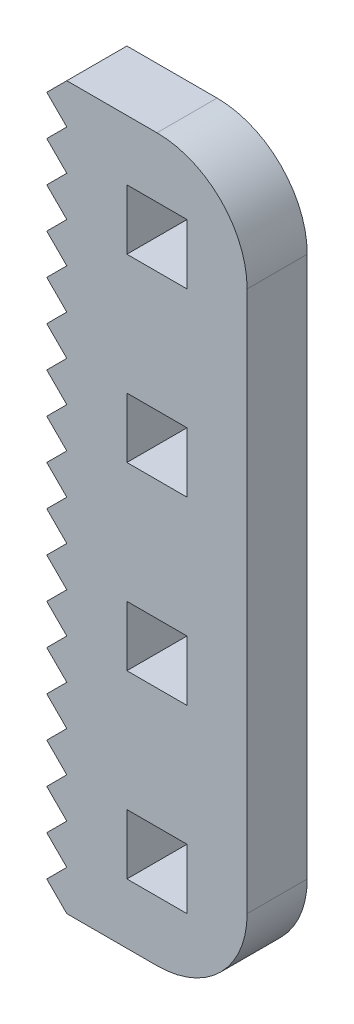
SolidWorks part; units mm, degrees
ref_plane "Alzado" through (0, 0, 0) normal (0, 0, 1) x (1, 0, 0)
ref_plane "Planta" through (0, 0, 0) normal (0, 1, 0) x (1, 0, 0)
ref_plane "Vista lateral" through (0, 0, 0) normal (1, 0, 0) x (0, 0, -1)
sketch "Model" plane through (0, 0, 0) normal (0, 0, 1) x (1, 0, 0)
  line L0 (9.9257, 288.1644) -> (8.9257, 289.1644)
  line L1 (8.9257, 289.1644) -> (9.9257, 290.1644)
  line L2 (9.9257, 286.1644) -> (8.9257, 287.1644)
  line L3 (8.9257, 287.1644) -> (9.9257, 288.1644)
  line L4 (9.9257, 284.1644) -> (8.9257, 285.1644)
  line L5 (8.9257, 285.1644) -> (9.9257, 286.1644)
  line L6 (9.9257, 282.1644) -> (8.9257, 283.1644)
  line L7 (8.9257, 283.1644) -> (9.9257, 284.1644)
  line L8 (9.9257, 280.1644) -> (8.9257, 281.1644)
  line L9 (8.9257, 281.1644) -> (9.9257, 282.1644)
  line L10 (9.9257, 278.1644) -> (8.9257, 279.1644)
  line L11 (8.9257, 279.1644) -> (9.9257, 280.1644)
  line L12 (9.9257, 276.1644) -> (8.9257, 277.1644)
  line L13 (8.9257, 277.1644) -> (9.9257, 278.1644)
  line L14 (9.9257, 274.1644) -> (8.9257, 275.1644)
  line L15 (8.9257, 275.1644) -> (9.9257, 276.1644)
  line L16 (9.9257, 272.1644) -> (8.9257, 273.1644)
  line L17 (8.9257, 273.1644) -> (9.9257, 274.1644)
  line L18 (9.9257, 270.1644) -> (8.9257, 271.1644)
  line L19 (8.9257, 271.1644) -> (9.9257, 272.1644)
  line L20 (9.9257, 268.1644) -> (8.9257, 269.1644)
  line L21 (8.9257, 269.1644) -> (9.9257, 270.1644)
  line L22 (9.9257, 266.1644) -> (8.9257, 267.1644)
  line L23 (8.9257, 267.1644) -> (9.9257, 268.1644)
  line L24 (9.9257, 264.1644) -> (8.9257, 265.1644)
  line L25 (8.9257, 265.1644) -> (9.9257, 266.1644)
  line L26 (9.9257, 262.1644) -> (8.9257, 263.1644)
  line L27 (8.9257, 263.1644) -> (9.9257, 264.1644)
  line L28 (9.9257, 260.1644) -> (8.9257, 261.1644)
  line L29 (8.9257, 261.1644) -> (9.9257, 262.1644)
  line L30 (9.9257, 258.1644) -> (8.9257, 259.1644)
  line L31 (8.9257, 259.1644) -> (9.9257, 260.1644)
  line L32 (9.9257, 256.1644) -> (8.9257, 257.1644)
  line L33 (8.9257, 257.1644) -> (9.9257, 258.1644)
  line L34 (9.9257, 254.1644) -> (8.9257, 255.1644)
  line L35 (8.9257, 255.1644) -> (9.9257, 256.1644)
  line L36 (12.9257, 287.1644) -> (12.9257, 284.1644)
  line L37 (15.9257, 287.1644) -> (12.9257, 287.1644)
  line L38 (15.9257, 284.1644) -> (15.9257, 287.1644)
  line L39 (12.9257, 284.1644) -> (15.9257, 284.1644)
  line L40 (12.9257, 278.1644) -> (12.9257, 275.1644)
  line L41 (15.9257, 278.1644) -> (12.9257, 278.1644)
  line L42 (15.9257, 275.1644) -> (15.9257, 278.1644)
  line L43 (12.9257, 275.1644) -> (15.9257, 275.1644)
  line L44 (12.9257, 260.1644) -> (12.9257, 257.1644)
  line L45 (15.9257, 260.1644) -> (12.9257, 260.1644)
  line L46 (15.9257, 257.1644) -> (15.9257, 260.1644)
  line L47 (12.9257, 257.1644) -> (15.9257, 257.1644)
  line L48 (12.9257, 269.1644) -> (12.9257, 266.1644)
  line L49 (15.9257, 269.1644) -> (12.9257, 269.1644)
  line L50 (15.9257, 266.1644) -> (15.9257, 269.1644)
  line L51 (12.9257, 266.1644) -> (15.9257, 266.1644)
  line L52 (18.9257, 258.6644) -> (18.9257, 285.6644)
  line L53 (14.4257, 290.1644) -> (9.9257, 290.1644)
  line L54 (14.4257, 254.1644) -> (9.9257, 254.1644)
  arc A0 (18.9257, 285.6644) -> (14.4257, 290.1644) centre (14.4257, 285.6644) ccw
  arc A1 (14.4257, 254.1644) -> (18.9257, 258.6644) centre (14.4257, 258.6644) ccw
extrude "Saliente-Extruir1" add sketch "Model" along normal blind 3
